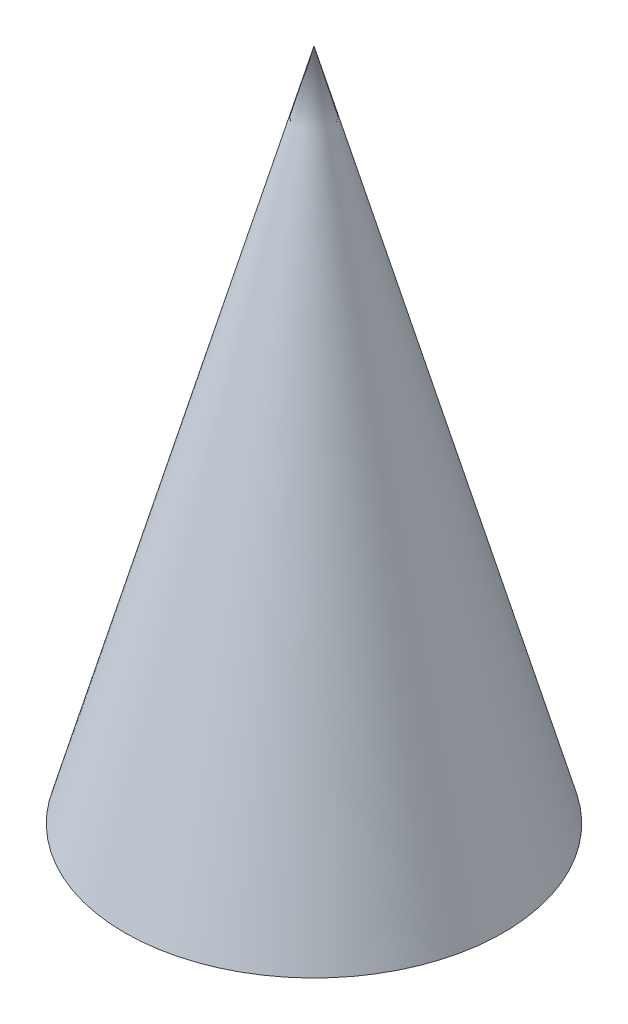
SolidWorks part; units mm, degrees
ref_plane "Front Plane" through (0, 0, 0) normal (0, 0, 1) x (1, 0, 0)
ref_plane "Top Plane" through (0, 0, 0) normal (0, 1, 0) x (1, 0, 0)
ref_plane "Right Plane" through (0, 0, 0) normal (1, 0, 0) x (0, 0, -1)
sketch "Sketch1" plane through (0, 0, 0) normal (0, 0, 1) x (1, 0, 0)
  line L0 (39.6, 0) -> (39.6, 80) construction
  line L1 (0, 0) -> (0, 589.6776) construction
  line L2 (38.1, 0) -> (38.1, 80) construction
  line L3 (0, 330) -> (0, 325.1029) construction
  line L4 (0, 0) -> (163.2597, 0) construction
  line L5 (38.1, 0) -> (39.6, 0) construction
  line L6 (0, 325.1029) -> (0, 271.7556)
  line L7 (0, 271.7556) -> (15, 271.7556)
  line L8 (15, 271.7556) -> (0, 325.1029)
  spline S0 degree 4 poles (-8.2172, 354.0002) (-8.1494, 353.8119) (-8.0142, 353.436) (-7.7464, 352.6901) (-7.2062, 351.1775) (-6.4789, 349.1293) (-5.5446, 346.4662) (-4.5162, 343.5025) (-3.4692, 340.4406) (-2.4903, 337.5478) (-1.5626, 334.7623) (-0.909, 332.7858) (-0.1595, 330.4915) (0.1448, 329.5553) (0.8619, 327.337) (1.48, 325.4029) (2.3193, 322.756) (3.4273, 319.2089) (4.7721, 314.8325) (6.2871, 309.7858) (7.9895, 303.961) (9.4331, 298.8777) (10.6481, 294.4982) (11.6396, 290.8519) (12.4234, 287.9276) (13.3884, 284.2716) (14.5251, 279.877) (16.1886, 273.2758) (17.9639, 265.9224) (19.6656, 258.5519) (21.6195, 249.6874) (23.4848, 240.8038) (25.2393, 231.8974) (26.8825, 222.97) (28.4366, 214.0267) (29.9015, 205.0683) (31.2545, 196.0922) (32.4955, 187.1001) (33.6468, 178.0961) (34.7082, 169.081) (35.6572, 160.0532) (36.4935, 151.0145) (37.1152, 143.4756) (37.5675, 137.4412) (37.9746, 131.4031) (38.3366, 125.3629) (38.6137, 120.0744) (38.823, 115.5417) (38.9786, 111.7609) (39.0917, 108.7406) (39.219, 104.9539) (39.3275, 101.1857) (39.417, 97.3848) (39.4878, 93.6314) (39.533, 90.5579) (39.567, 87.6237) (39.5868, 84.8177) (39.5967, 82.8056) (39.6003, 80.4721) (39.6002, 79.4963) (39.5965, 77.113) (39.5861, 75.0596) (39.5652, 72.1674) (39.5293, 69.1569) (39.4812, 65.9684) (39.4209, 62.8765) (39.3573, 60.0957) (39.3002, 57.9538) (39.2552, 56.3714) (39.2317, 55.5905) (39.2197, 55.197) (39.2136, 54.9998) knots 0 0 0 0 0 0.002619 0.005238 0.010476 0.020951 0.031427 0.041903 0.052253 0.062603 0.072953 0.078128 0.083304 0.088271 0.093239 0.103175 0.11311 0.123046 0.142917 0.162788 0.18266 0.202531 0.212466 0.222402 0.232338 0.242273 0.262144 0.282016 0.321758 0.341629 0.3615 0.401243 0.440985 0.460857 0.480728 0.52047 0.560213 0.580084 0.599955 0.639697 0.67944 0.699311 0.719182 0.739053 0.758925 0.778796 0.798667 0.808603 0.818538 0.828474 0.838409 0.858281 0.868216 0.878152 0.888087 0.898023 0.907959 0.912926 0.917894 0.922995 0.928095 0.938296 0.948496 0.958697 0.969023 0.979348 0.989674 0.994837 0.997419 1 1 1 1 1 construction
  spline S1 degree 4 poles (0, 330) (0.0976, 329.6998) (0.293, 329.0969) (0.8619, 327.337) (1.48, 325.4029) (2.3193, 322.756) (3.4273, 319.2089) (4.7721, 314.8325) (6.2871, 309.7858) (7.9895, 303.961) (9.4331, 298.8777) (10.6481, 294.4982) (11.6396, 290.8519) (12.4234, 287.9276) (13.3884, 284.2716) (14.5251, 279.877) (16.1886, 273.2758) (17.9639, 265.9224) (19.6656, 258.5519) (21.6195, 249.6874) (23.4848, 240.8038) (25.2393, 231.8974) (26.8825, 222.97) (28.4366, 214.0267) (29.9015, 205.0683) (31.2545, 196.0922) (32.4955, 187.1001) (33.6468, 178.0961) (34.7082, 169.081) (35.6572, 160.0532) (36.4935, 151.0145) (37.1152, 143.4756) (37.5675, 137.4412) (37.9746, 131.4031) (38.3366, 125.3629) (38.6137, 120.0744) (38.823, 115.5417) (38.9786, 111.7609) (39.0917, 108.7406) (39.219, 104.9539) (39.3275, 101.1857) (39.417, 97.3848) (39.4878, 93.6314) (39.533, 90.5579) (39.567, 87.6237) (39.5868, 84.8177) (39.5967, 82.8056) (39.5995, 80.9487) (39.6, 80.3157) (39.6, 80) knots 0.083304 0.083304 0.083304 0.083304 0.083304 0.088271 0.093239 0.103175 0.11311 0.123046 0.142917 0.162788 0.18266 0.202531 0.212466 0.222402 0.232338 0.242273 0.262144 0.282016 0.321758 0.341629 0.3615 0.401243 0.440985 0.460857 0.480728 0.52047 0.560213 0.580084 0.599955 0.639697 0.67944 0.699311 0.719182 0.739053 0.758925 0.778796 0.798667 0.808603 0.818538 0.828474 0.838409 0.858281 0.868216 0.878152 0.888087 0.898023 0.907959 0.912926 0.917894 0.917894 0.917894 0.917894 0.917894 construction
  spline S2 degree 1 poles (-1.4266, 329.5364) (38.1, 80) knots 0 0 1 1 construction
  spline S3 degree 3 poles (-1.4266, 329.5364) (-1.383, 329.4024) (-1.2989, 329.1432) (-1.1081, 328.554) (-0.8243, 327.6757) (-0.4974, 326.66) (-0.2579, 325.9116) (-0.0684, 325.3176) (0.0486, 324.9503) (0.2006, 324.4721) (0.5038, 323.5167) (1.1954, 321.326) (2.1624, 318.219) (3.7193, 313.134) (5.5999, 306.8222) (9.493, 293.2761) (12.7545, 280.9434) (15.3146, 270.4722) (20.673, 248.1978) (29.0028, 206.2449) (34.5733, 159.1795) (36.7511, 127.5431) (37.3996, 114.3427) (37.7627, 103.7831) (37.9087, 97.8304) (37.9816, 93.8801) (38.0132, 91.8818) (38.04, 89.9069) (38.0619, 87.9504) (38.0761, 86.2546) (38.085, 84.9378) (38.0905, 83.982) (38.0947, 83.024) (38.0978, 81.9582) (38.0993, 81.033) (38.0999, 80.4133) (38.1, 80.1409) (38.1, 80) knots 0.083304 0.083304 0.083304 0.083304 0.084934 0.086564 0.089824 0.093084 0.096344 0.097819 0.099449 0.100264 0.102864 0.109385 0.122425 0.135466 0.161546 0.187627 0.274449 0.28749 0.29401 0.500599 0.709247 0.761408 0.81357 0.839651 0.865732 0.872253 0.878773 0.885293 0.891813 0.898334 0.901594 0.904854 0.908114 0.911374 0.914634 0.916264 0.917894 0.917894 0.917894 0.917894 only from (0, 325.1029) to (38.1, 80) construction
  dimension "D1" = 80
  dimension "D2" = 39.6
  dimension "D4" = 15
  dimension "D3" = 1.5
revolve "Revolve1" add sketch "Sketch1" angle 360 about L1
sketch "Sketch2" plane through (0, 271.7556, 0) normal (0, -1, 0) x (1, 0, 0)
  circle A0 centre (0, 0) radius 2.5
  dimension "D1" = 5
extrude "Cut-Extrude1" cut sketch "Sketch2" against normal blind 20
sketch "Sketch4" plane through (0, 0, 0) normal (0, 0, 1) x (1, 0, 0)
  line L0 (0, 271.7556) -> (0, 328.1412) construction
  line L1 (-15, 271.7556) -> (15, 271.7556) construction
  line L2 (15, 271.7556) -> (0, 325.1029) construction
  line L3 (15, 271.7556) -> (0, 325.1029)
  line L4 (0, 325.1029) -> (0, 321.4085)
  line L5 (15, 271.7556) -> (13.9612, 271.7556)
  line L6 (13.9612, 271.7556) -> (0, 321.4085)
  line L7 (14.0373, 271.4849) -> (-0.9627, 324.8322) construction
  dimension "D1" = 1
revolve "Cut-Revolve1" cut sketch "Sketch4" angle 360 about L0
